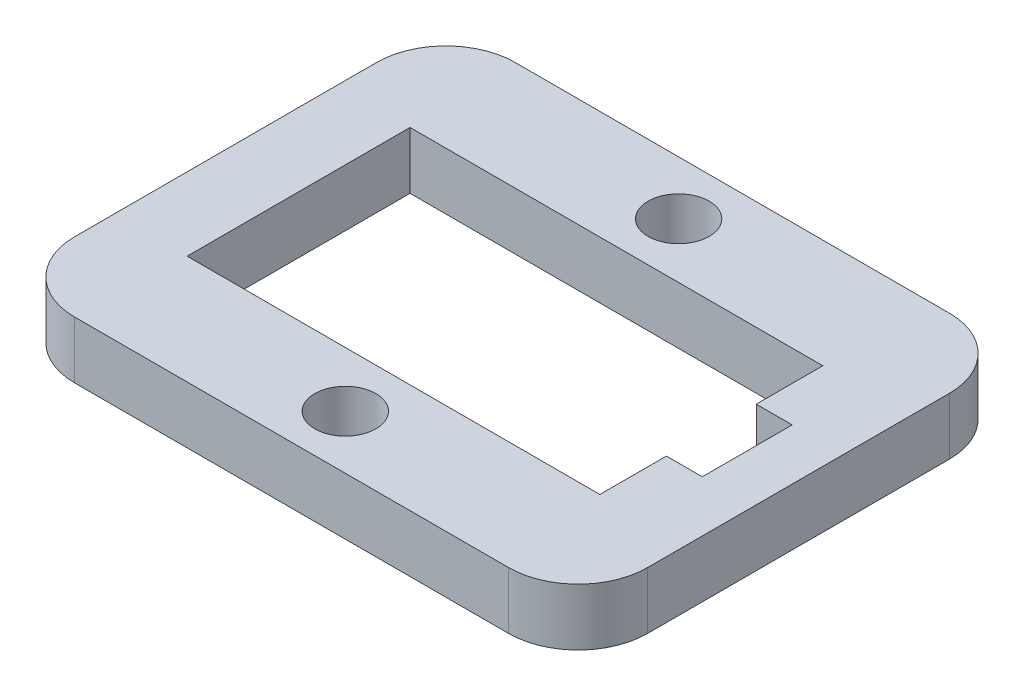
SolidWorks part; units mm, degrees
material "Acrylic (Medium-high impact)"
ref_plane "Front Plane" through (0, 0, 0) normal (0, 0, 1) x (1, 0, 0)
ref_plane "Top Plane" through (0, 0, 0) normal (0, 1, 0) x (1, 0, 0)
ref_plane "Right Plane" through (0, 0, 0) normal (1, 0, 0) x (0, 0, -1)
sketch "Sketch1" plane through (0, 0, 0) normal (0, 1, 0) x (1, 0, 0)
  line L0 (-2.4168, 9.7093) -> (-25.3759, 9.7093)
  line L1 (-25.3759, 9.7093) -> (-25.3759, -2.691)
  line L2 (-25.3759, -2.691) -> (-2.4168, -2.691)
  line L3 (-2.4168, -2.691) -> (-2.4168, 1.0091)
  line L4 (-2.4168, 1.0091) -> (-0.4201, 1.0091)
  line L5 (-0.4201, 1.0091) -> (-0.4201, 6.0092)
  line L6 (-0.4201, 6.0092) -> (-2.4168, 6.0092)
  line L7 (-2.4168, 6.0092) -> (-2.4168, 9.7093)
  line L8 (-1.4252, 15.7631) -> (-25.5836, 15.7631)
  line L9 (-29.4395, 11.9072) -> (-29.4395, -4.8889)
  line L10 (-25.5766, -8.7517) -> (-1.4322, -8.7517)
  line L11 (2.4307, -4.8889) -> (2.4307, 11.9072)
  line L12 (-13.5079, 18.1727) -> (-13.5079, -12.9202) construction
  line L13 (-29.4395, 3.5092) -> (2.4307, 3.5092) construction
  arc A0 (-25.5836, 15.7631) -> (-29.4395, 11.9072) centre (-25.5836, 11.9072) ccw
  arc A1 (-29.4395, -4.8889) -> (-25.5766, -8.7517) centre (-25.5766, -4.8889) ccw
  arc A2 (-1.4322, -8.7517) -> (2.4307, -4.8889) centre (-1.4322, -4.8889) ccw
  arc A3 (2.4307, 11.9072) -> (-1.4252, 15.7631) centre (-1.4252, 11.9072) ccw
  circle A4 centre (-13.5079, 12.7792) radius 1.7
  circle A5 centre (-13.5079, -5.7608) radius 1.7
  point P26 (-13.5079, 12.7792)
  point P27 (-13.5079, -5.7608)
  dimension "D1" = 3.4
  dimension "D2" = 22.9592
  dimension "D3" = 11.868
  dimension "D6" = 18.54
  dimension "D7" = 9.27
  dimension "D4" = 12.4003
  dimension "D5" = 6.2002
extrude "Boss-Extrude1" add sketch "Sketch1" along normal blind 3.175
